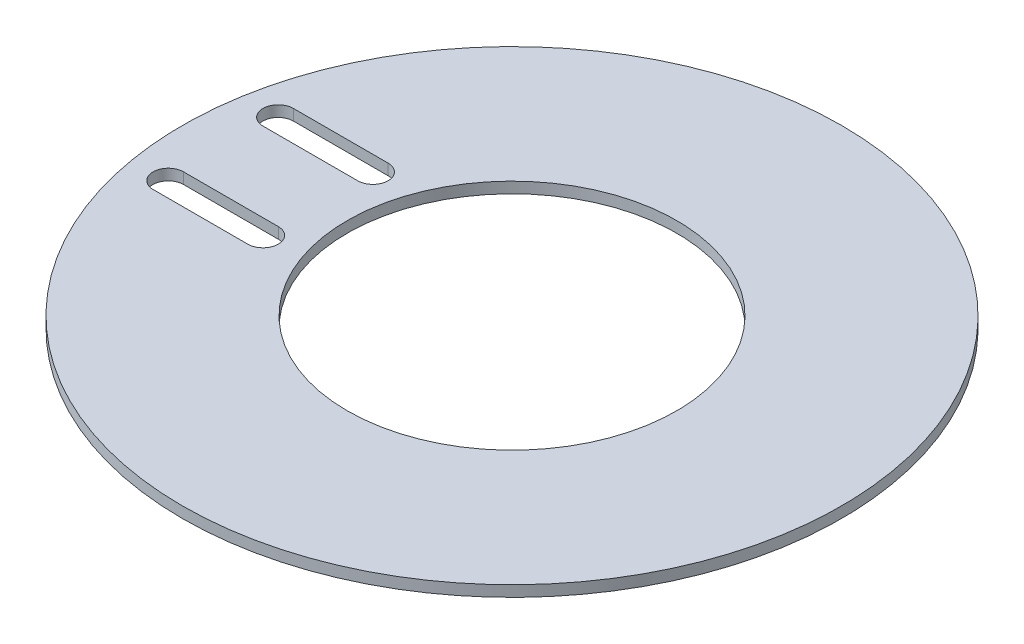
SolidWorks part; units mm, degrees
ref_plane "Front Plane" through (0, 0, 0) normal (0, 0, 1) x (1, 0, 0)
ref_plane "Top Plane" through (0, 0, 0) normal (0, 1, 0) x (1, 0, 0)
ref_plane "Right Plane" through (0, 0, 0) normal (1, 0, 0) x (0, 0, -1)
sketch "Sketch1" plane through (0, 0, 0) normal (0, 1, 0) x (1, 0, 0)
  line L0 (-123.8878, 0) -> (189.6043, 0) construction
  line L1 (189.6043, 0) -> (0, 0) construction
  line L2 (0, 0) -> (0, 100.2785) construction
  line L3 (0, 100.2785) -> (0, -105.8766) construction
  line L4 (-76.2, 0) -> (-55.8137, 0) construction
  line L5 (-55.8137, 0) -> (-55.8137, 12.7) construction
  line L6 (-55.8137, 0) -> (-55.8137, -12.7) construction
  line L7 (-66.7665, 12.7) -> (-44.8609, 12.7) construction
  line L8 (-66.7665, 16.2263) -> (-44.8609, 16.2263)
  line L9 (-66.7665, 9.1737) -> (-44.8609, 9.1737)
  line L10 (-66.7665, -12.7) -> (-44.8609, -12.7) construction
  line L11 (-66.7665, -16.2263) -> (-44.8609, -16.2263)
  line L12 (-66.7665, -9.1737) -> (-44.8609, -9.1737)
  circle A0 centre (0, 0) radius 76.2
  circle A1 centre (0, 0) radius 38.1
  arc A2 (-66.7665, 16.2263) -> (-66.7665, 9.1737) centre (-66.7665, 12.7) ccw
  arc A3 (-44.8609, 9.1737) -> (-44.8609, 16.2263) centre (-44.8609, 12.7) ccw
  arc A4 (-66.7665, -16.2263) -> (-66.7665, -9.1737) centre (-66.7665, -12.7) cw
  arc A5 (-44.8609, -9.1737) -> (-44.8609, -16.2263) centre (-44.8609, -12.7) cw
  point P14 (-55.8137, 12.7)
  point P21 (-55.8137, -12.7)
extrude "Boss-Extrude1" add sketch "Sketch1" along normal blind 2.54
scale "Scale1" scale about centroid uniform scaling yes scale factor 3
scale "Scale2" scale about centroid uniform scaling yes scale factor 3
scale "Scale3" scale about centroid uniform scaling yes scale factor 3
scale "Scale4" scale about centroid uniform scaling yes scale factor 0.88
sketch "Sketch2" plane through (0, 0, 385.5368) normal (0, 0, -1) x (-1, 0, 0)
  circle A0 centre (1561.4822, 0) radius 23.118
  circle A1 centre (1144.3672, 0) radius 23.1547
sketch "Sketch4" plane through (0, 0, -385.5368) normal (0, 0, 1) x (1, 0, 0)
  circle A1 centre (-1144.3672, 0) radius 23.1547
  circle A2 centre (-1561.4822, 0) radius 23.118
sketch "Sketch5" plane through (0, 31.4452, 0) normal (0, 1, 0) x (1, 0, 0)
  line L0 (-1847.5029, 0) -> (1773.5211, 0) construction
  circle A0 centre (-36.9909, 0) radius 1810.512 construction
  point P6 (1773.5211, 0)
  point P7 (-1847.5029, 0)
sketch "Sketch6" plane through (0, 31.4452, 0) normal (0, 1, 0) x (1, 0, 0)
  line L0 (-36.9909, -1810.512) -> (-36.9909, 1810.512) construction
  circle A0 centre (-36.9909, 0) radius 1810.512 construction
